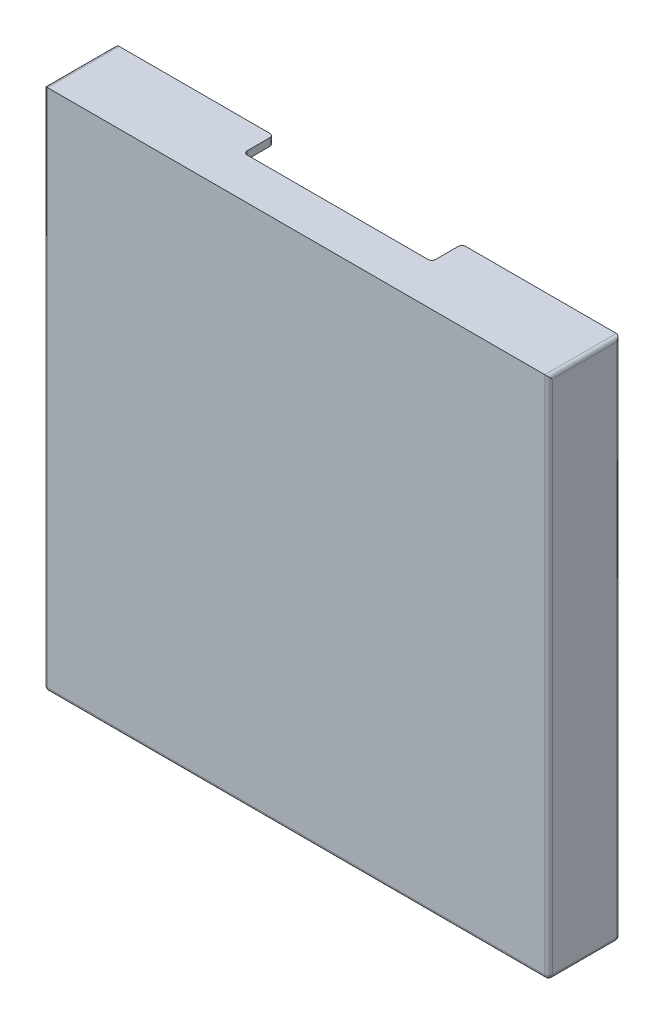
SolidWorks part; units mm, degrees
ref_plane "前视基准面" through (0, 0, 0) normal (0, 0, 1) x (1, 0, 0)
ref_plane "上视基准面" through (0, 0, 0) normal (0, 1, 0) x (1, 0, 0)
ref_plane "右视基准面" through (0, 0, 0) normal (1, 0, 0) x (0, 0, -1)
sketch "草图1" plane through (0, 0, 0) normal (0, 1, 0) x (1, 0, 0)
  line L1 (134, -19) -> (-134, -19)
  line L2 (134, -19) -> (134, 19)
  line L3 (134, 19) -> (-134, 19)
  line L4 (-134, -19) -> (-134, 19)
  line L5 (134, -19) -> (-134, 19) construction
  line L6 (134, 19) -> (-134, -19) construction
  point P0 (0, 0)
  dimension "D1" = 268
  dimension "D2" = 38
extrude "凸台-拉伸1" add sketch "草图1" along normal blind 278
sketch "草图2" plane through (0, 0, -19) normal (0, 0, -1) x (-1, 0, 0)
  line L14 (-130, 4) -> (130, 4)
  line L15 (130, 4) -> (130, 274)
  line L16 (130, 274) -> (-130, 274)
  line L17 (-130, 274) -> (-130, 4)
  line L18 (-130, 4) -> (130, 4)
  line L19 (130, 4) -> (130, 274)
  line L20 (130, 274) -> (-130, 274)
  line L21 (-130, 274) -> (-130, 4)
  dimension "D1" = 4
extrude "切除-拉伸1" cut sketch "草图2" against normal offset from surface (36 mm away) 2 up to face at (0, 139, 19)
sketch "草图3" plane through (0, 278, 0) normal (0, 1, 0) x (1, 0, 0)
  line L0 (0, 19) -> (0, -19) construction
  line L1 (134, 19) -> (-134, 19) construction
  line L2 (-134, -19) -> (134, -19) construction
  line L3 (50, 19) -> (-50, 19)
  line L4 (-50, 19) -> (-50, 3)
  line L5 (-50, 3) -> (50, 3)
  line L6 (50, 19) -> (50, 3)
  point P10 (0, 3)
  dimension "D1" = 16
  dimension "D2" = 100
extrude "切除-拉伸2" cut sketch "草图3" against normal up to next
fillet "圆角1" radius 2 14 edges at (134, 278, 0) (134, 0, 0) (-134, 0, 0) (-134, 278, 0) (0, 0, -19) (134, 139, -19) (-134, 139, -19) (0, 0, 19) (134, 139, 19) (-134, 139, 19) (-50, 276, -3) (50, 276, -3) (50, 276, -19) (-50, 276, -19)
sketch "草图4" plane through (0, 0, 17) normal (0, 0, -1) x (-1, 0, 0)
  line L0 (-68, 274) -> (-68, 4)
  line L1 (-130, 274) -> (130, 274) construction
  line L2 (130, 4) -> (-130, 4) construction
  line L3 (-66, 274) -> (-66, 4)
  line L4 (-130, 4) -> (-130, 274) construction
  line L7 (-130, 274) -> (-130, 4)
  line L8 (-130, 4) -> (130, 4)
  line L9 (130, 4) -> (130, 274)
  line L10 (130, 274) -> (-130, 274)
  line L12 (-68, 4) -> (-66, 4)
  line L14 (-66, 274) -> (-68, 274)
  dimension "D2" = 2
  dimension "D3" = 62
  dimension "D1" = 0
extrude "凸台-拉伸2" add sketch "草图4" along normal up to surface (36 mm away) up to face at (0, 185, -19)
pattern_linear "阵列(线性)1" count 3 spacing 66 along (-1, 0, 0) of "凸台-拉伸2"
sketch "草图5" plane through (0, 0, 17) normal (0, 0, -1) x (-1, 0, 0)
  line L0 (-130, 210) -> (130, 210)
  line L1 (-130, 208) -> (130, 208)
  line L2 (-52, 274) -> (-66, 274) construction
  line L3 (-130, 274) -> (-130, 4) construction
  line L4 (66, 274) -> (66, 4)
  line L6 (130, 4) -> (130, 274)
  line L7 (130, 274) -> (66, 274)
  line L10 (130, 208) -> (130, 210)
  line L12 (-130, 210) -> (-130, 208)
  line L15 (66, 4) -> (130, 4)
  dimension "D2" = 2
  dimension "D3" = 64
  dimension "D1" = 0
extrude "凸台-拉伸3" add sketch "草图5" along normal up to surface (36 mm away) up to face at (0.5, 173.5, -19)
sketch "草图7" plane through (0, 0, 0) normal (-1, 0, 0) x (0, 0, 1)
  line L0 (-19, 274) -> (-19, 210) construction
  line L1 (-19, 274) -> (-3, 274) construction
  line L2 (-19, 274) -> (-19, 258)
  line L3 (-19, 274) -> (-3, 274)
  arc A0 (-3, 274) -> (-19, 258) centre (-19, 274) cw
  point P5 (-19, 257.492)
  point P6 (-19, 254.6847)
  point P7 (0, 0)
  point P8 (0, 0)
extrude "切除-拉伸4" cut sketch "草图7" against normal up to surface (2 mm away) up to face at (2, 248.4, -1.4)
fillet "圆角2" radius 2 1 edges at (1, 258, -19)
pattern_linear "阵列(线性)2" count 3 spacing 70 along (0, -1, 0) of "凸台-拉伸3"
